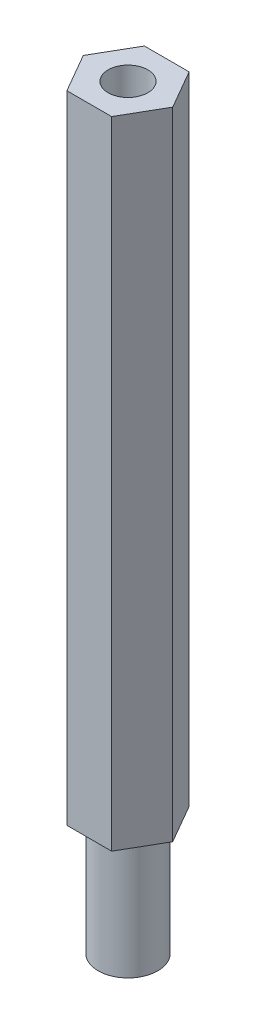
SolidWorks part; units mm, degrees
ref_plane "前视基准面" through (0, 0, 0) normal (0, 0, 1) x (1, 0, 0)
ref_plane "上视基准面" through (0, 0, 0) normal (0, 1, 0) x (1, 0, 0)
ref_plane "右视基准面" through (0, 0, 0) normal (1, 0, 0) x (0, 0, -1)
sketch "草图1" plane through (0, 0, 0) normal (0, 1, 0) x (1, 0, 0)
  line L1 (2.25, 0) -> (1.125, 1.9486)
  line L2 (1.125, 1.9486) -> (-1.125, 1.9486)
  line L3 (-1.125, 1.9486) -> (-2.25, 0)
  line L4 (-2.25, 0) -> (-1.125, -1.9486)
  line L5 (-1.125, -1.9486) -> (1.125, -1.9486)
  line L6 (1.125, -1.9486) -> (2.25, 0)
  circle A0 centre (0, 0) radius 2.25 construction
  circle A1 centre (0, 0) radius 1.9486 construction
  point P3 (0, 0)
  dimension "D1" = 4.5
extrude "凸台-拉伸1" add sketch "草图1" along normal blind 32
sketch "草图2" plane through (0, 0, 0) normal (0, -1, 0) x (1, 0, 0)
  circle A0 centre (0, 0) radius 1.5
  dimension "D1" = 3
extrude "凸台-拉伸2" add sketch "草图2" along normal blind 6 contours A0
sketch "草图3" plane through (0, 32, 0) normal (0, 1, 0) x (1, 0, 0)
  circle A0 centre (0, 0) radius 1
  dimension "D1" = 2
extrude "切除-拉伸1" cut sketch "草图3" against normal blind 10 contours A0
